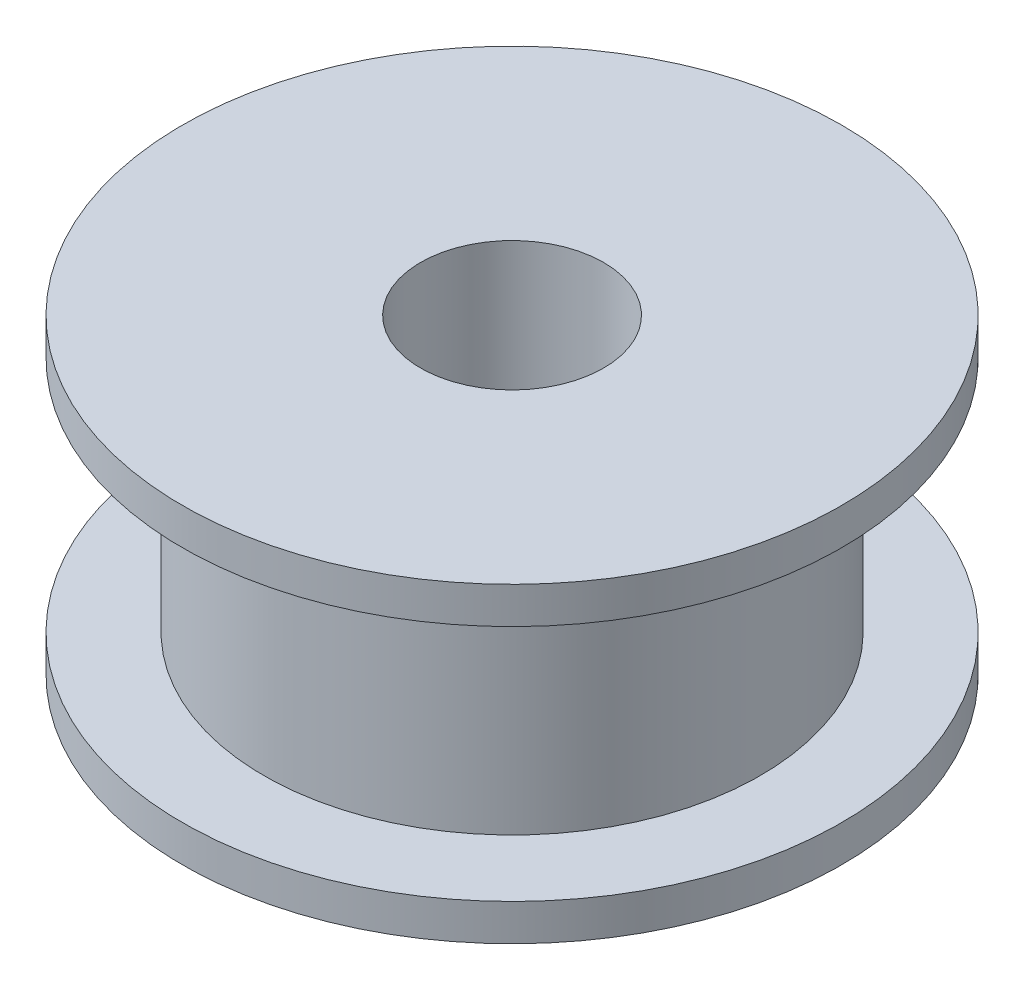
SolidWorks part; units mm, degrees
ref_plane "Front Plane" through (0, 0, 0) normal (0, 0, 1) x (1, 0, 0)
ref_plane "Top Plane" through (0, 0, 0) normal (0, 1, 0) x (1, 0, 0)
ref_plane "Right Plane" through (0, 0, 0) normal (1, 0, 0) x (0, 0, -1)
sketch "Sketch1" plane through (0, 0, 0) normal (0, 0, 1) x (1, 0, 0)
  line L0 (0, 0) -> (0, 4.25) construction
  line L1 (0, 4.25) -> (2.5, 4.25) construction
  line L2 (2.5, 4.25) -> (9, 4.25)
  line L3 (9, 4.25) -> (9, 3.25)
  line L4 (9, 3.25) -> (6.7778, 3.25)
  line L5 (6.7778, 3.25) -> (6.7778, -3.25)
  line L6 (2.5, 4.25) -> (2.5, -4.25)
  line L7 (2.5, 0) -> (6.7778, 0) construction
  line L8 (9, -3.25) -> (6.7778, -3.25)
  line L9 (9, -4.25) -> (9, -3.25)
  line L10 (2.5, -4.25) -> (9, -4.25)
  dimension "D1" = 2.5
  dimension "D2" = 4.25
  dimension "D3" = 6.5
  dimension "D4" = 1
revolve "Revolve1" add sketch "Sketch1" angle 360 about L0
